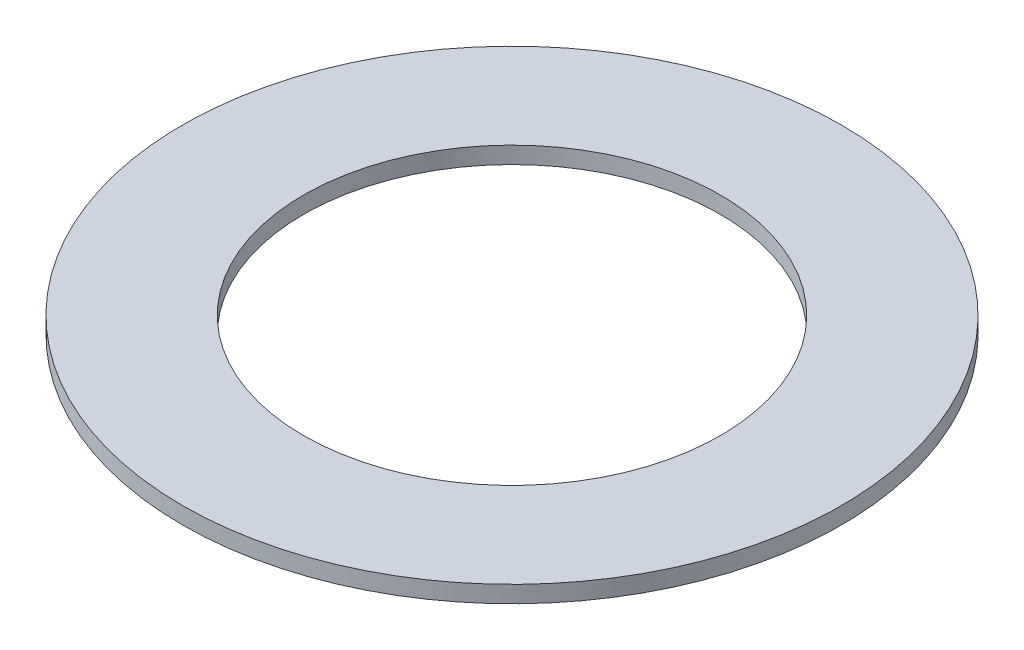
SolidWorks part; units mm, degrees
ref_plane "Front Plane" through (0, 0, 0) normal (0, 0, 1) x (1, 0, 0)
ref_plane "Top Plane" through (0, 0, 0) normal (0, 1, 0) x (1, 0, 0)
ref_plane "Right Plane" through (0, 0, 0) normal (1, 0, 0) x (0, 0, -1)
sketch "Sketch1" plane through (0, 0, 0) normal (0, 1, 0) x (1, 0, 0)
  circle A0 centre (0, 0) radius 78.35
  circle A1 centre (0, 0) radius 49.55
  dimension "D1" = 156.7
  dimension "D2" = 99.1
extrude "Boss-Extrude1" add sketch "Sketch1" along normal blind 4
